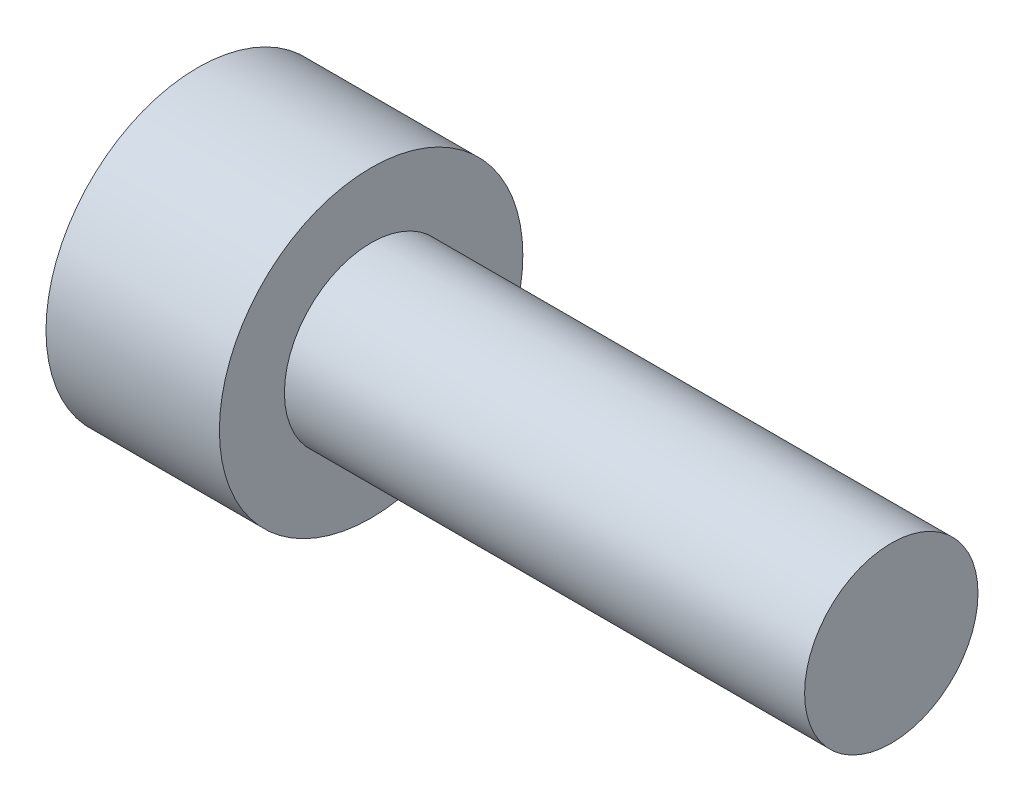
SolidWorks part; units mm, degrees
ref_plane "Front Plane" through (0, 0, 0) normal (0, 0, 1) x (1, 0, 0)
ref_plane "Top Plane" through (0, 0, 0) normal (0, 1, 0) x (1, 0, 0)
ref_plane "Right Plane" through (0, 0, 0) normal (1, 0, 0) x (0, 0, -1)
sketch "Sketch1" plane through (0, 0, 0) normal (0, 0, 1) x (1, 0, 0)
  line L0 (0, 0) -> (16, 0) construction
  line L3 (0, 0) -> (0, 3.5)
  line L4 (0, 3.5) -> (4, 3.5)
  line L5 (4, 2) -> (4, 3.5)
  line L6 (4, 2) -> (16, 2)
  line L8 (0, 0) -> (16, 0)
  line L9 (16, 2) -> (16, 0)
  dimension "CS_A" = 7
  dimension "CS_E" = 4
  dimension "CS_L" = 12
  dimension "CS_M" = 4
revolve "Revolve1" add sketch "Sketch1" angle 360 about L0
cosmetic thread "Cosmetic Thread1" parameters "CS_D_s"=3.242
sketch "Sketch2" plane through (0, 0, 0) normal (0, 0, 1) x (1, 0, 0)
  line L0 (0, 0) -> (16, 0) construction
  line L1 (0, 3.5) -> (0, -3.5) construction
  line L2 (16, -2) -> (16, 2) construction
  line L3 (0, 1.5) -> (2, 1.5)
  line L4 (2, 1.5) -> (2.866, 0)
  line L5 (0, 1.5) -> (0, 0)
  line L6 (0, 0) -> (2.866, 0)
  dimension "D1" = 60
  dimension "CS_T_s" = 2
  dimension "CS_B" = 3
revolve "Cut-Revolve1" cut sketch "Sketch2" angle 360 about L0
sketch "Sketch3" plane through (0, 0, 0) normal (-1, 0, 0) x (0, 0, 1)
  line L0 (0, 0) -> (0, 3.5) construction
  line L1 (0, -1.7321) -> (1.5, -0.866)
  line L2 (1.5, -0.866) -> (1.5, 0.866)
  line L3 (1.5, 0.866) -> (0, 1.7321)
  line L4 (0, 1.7321) -> (-1.5, 0.866)
  line L5 (-1.5, 0.866) -> (-1.5, -0.866)
  line L6 (-1.5, -0.866) -> (0, -1.7321)
  circle A0 centre (0, 0) radius 1.5 construction
  circle A1 centre (0, 0) radius 3.5 construction
  circle A2 centre (0, 0) radius 1.5 construction
extrude "Cut-Extrude1" cut sketch "Sketch3" against normal blind 2
